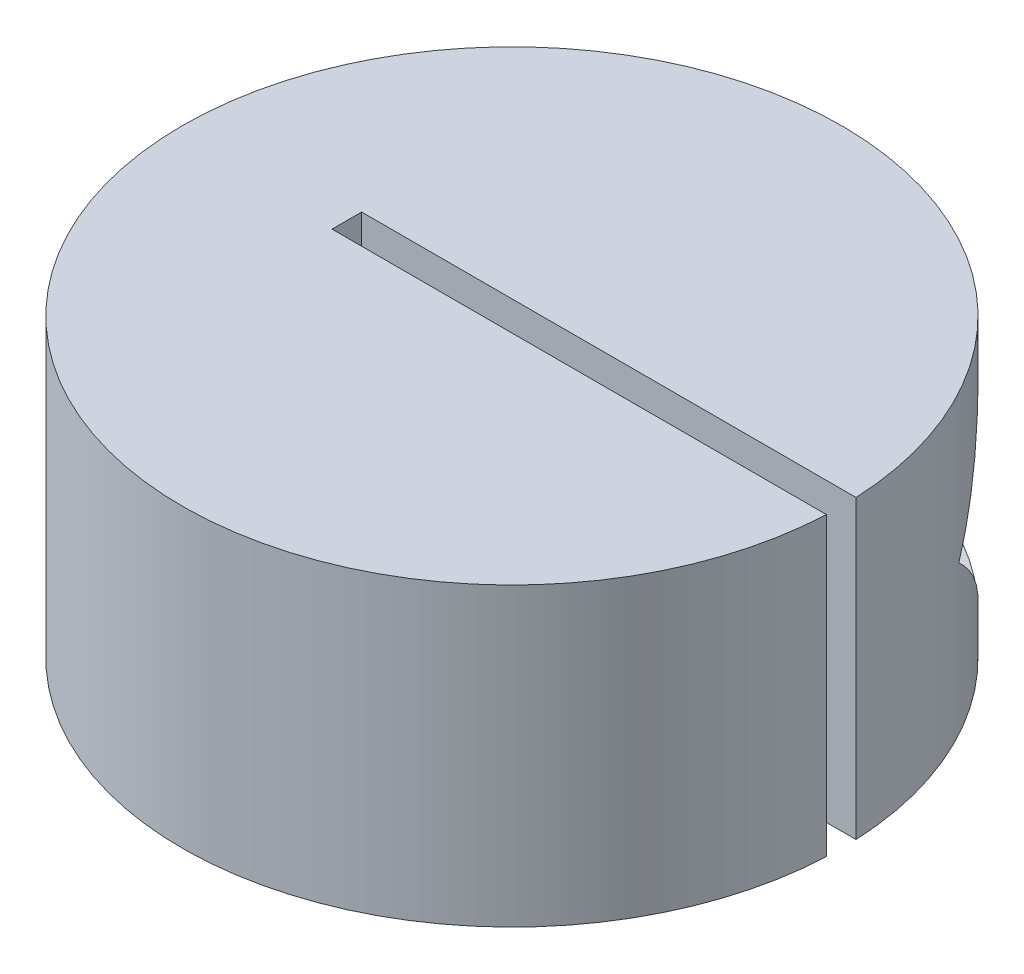
SolidWorks part; units mm, degrees
ref_plane "Front Plane" through (0, 0, 0) normal (0, 0, 1) x (1, 0, 0)
ref_plane "Top Plane" through (0, 0, 0) normal (0, 1, 0) x (1, 0, 0)
ref_plane "Right Plane" through (0, 0, 0) normal (1, 0, 0) x (0, 0, -1)
sketch "Sketch1" plane through (0, 0, 0) normal (0, 1, 0) x (1, 0, 0)
  circle A0 centre (0, 0) radius 11.125
  dimension "D1" = 22.25
extrude "Boss-Extrude1" add sketch "Sketch1" along normal blind 10
sketch "Sketch2" plane through (0, 0, 0) normal (0, 0, 1) x (1, 0, 0)
  line L0 (0, 5) -> (11.125, 5) construction
  line L1 (11.125, 10) -> (-11.125, 10) construction
  line L2 (0, 0) -> (0, 10) construction
  line L3 (11.125, 0) -> (11.125, 10) construction
  line L5 (3.4692, 1.342) -> (7.6838, 1.3581)
  line L6 (7.6838, 1.3581) -> (9.7771, 5.0161)
  line L7 (9.7771, 5.0161) -> (7.6558, 8.658)
  line L8 (7.6558, 8.658) -> (3.4412, 8.6419)
  line L9 (3.4412, 8.6419) -> (1.3479, 4.9839)
  line L10 (1.3479, 4.9839) -> (3.4692, 1.342)
  circle A0 centre (5.5625, 5) radius 3.65 construction
  point P1 (0, 10)
  dimension "D1" = 7.3
  dimension "D2" = 4.2146
extrude "Cut-Extrude1" cut sketch "Sketch2" against normal through all
sketch "Sketch3" plane through (0, 0, 0) normal (0, 1, 0) x (1, 0, 0)
  line L0 (-5.5735, 0.5) -> (-5.5735, -0.5)
  line L5 (-5.5735, -0.5) -> (11.4265, -0.5)
  line L6 (11.4265, -0.5) -> (11.4265, 0.5)
  line L12 (11.4265, 0.5) -> (-5.5735, 0.5)
  line L13 (-5.5735, 0) -> (11.4265, 0) construction
  point P3 (-0.5735, 0.5)
  point P7 (0, 0)
  point P8 (0, 0)
  dimension "D1" = 5
  dimension "D2" = 12
  dimension "D3" = 1
extrude "Cut-Extrude2" cut sketch "Sketch3" along normal through all
